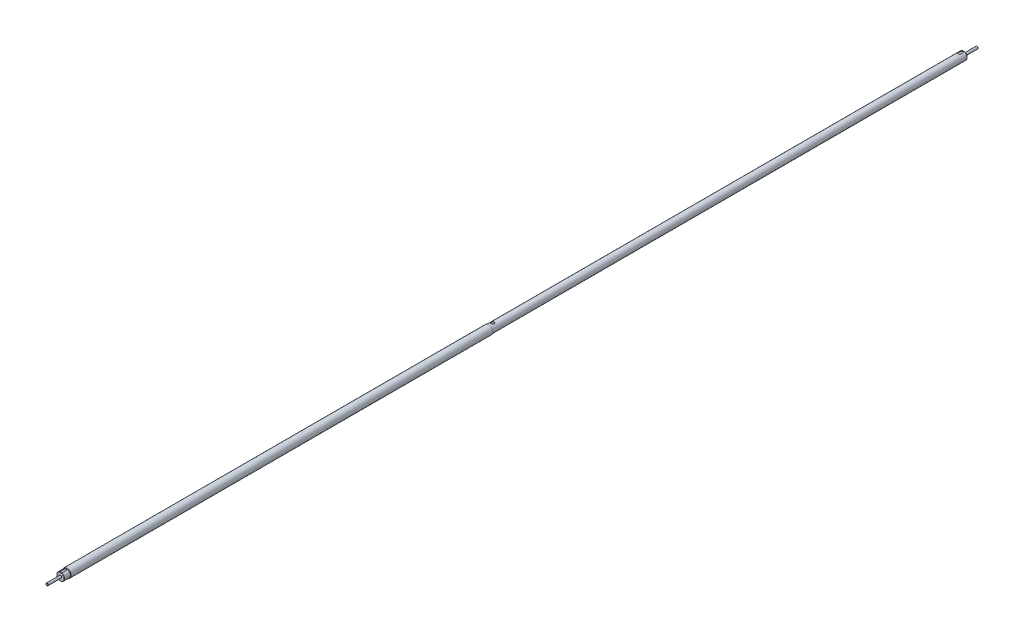
SolidWorks part; units mm, degrees
ref_plane "Спереди" through (0, 0, 0) normal (0, 0, 1) x (1, 0, 0)
ref_plane "Сверху" through (0, 0, 0) normal (0, 1, 0) x (1, 0, 0)
ref_plane "Справа" through (0, 0, 0) normal (1, 0, 0) x (0, 0, -1)
sketch "Эскиз1" plane through (0, 0, 0) normal (1, 0, 0) x (0, 0, -1)
  line L0 (0, 0) -> (0, 3)
  line L1 (0, 3) -> (35, 3)
  line L2 (35, 3) -> (35, 10)
  line L3 (35, 10) -> (51, 10)
  line L4 (51, 10) -> (51, 11)
  line L5 (51, 11) -> (1145, 11)
  line L6 (1145, 11) -> (1145, 10)
  line L7 (1145, 10) -> (1185, 10)
  line L8 (0, 0) -> (2410, 0)
  line L9 (2410, 0) -> (2410, 3)
  line L10 (2410, 3) -> (2375, 3)
  line L11 (2375, 3) -> (2375, 10)
  line L12 (2375, 10) -> (1185, 10)
  dimension "D1" = 3
  dimension "D2" = 7
  dimension "D3" = 35
  dimension "D4" = 16
  dimension "D5" = 1
  dimension "D6" = 1094
  dimension "D7" = 1
  dimension "D8" = 40
  dimension "D9" = 2410
  dimension "D10" = 3
  dimension "D11" = 35
  dimension "D12" = 7
revolve "Повернуть1" add sketch "Эскиз1" angle 360 about L8
ref_plane "Плоскость1" through (0, 10, 0) normal (0, 1, 0) x (1, 0, 0)
sketch "Эскиз2" plane through (0, 10, 0) normal (0, 1, 0) x (1, 0, 0)
  line L0 (0, 47) -> (0, 39) construction
  line L1 (3, 47) -> (3, 39)
  line L2 (-3, 47) -> (-3, 39)
  line L3 (-10, 35) -> (10, 35) construction
  arc A0 (3, 47) -> (-3, 47) centre (0, 47) ccw
  arc A1 (-3, 39) -> (3, 39) centre (0, 39) ccw
  point P3 (0, 43)
  dimension "D1" = 6
  dimension "D2" = 8
  dimension "D3" = 4
extrude "Вырез-Вытянуть1" cut sketch "Эскиз2" against normal blind 1.2 contours L1 A1 L2 A0
ref_plane "Плоскость2" through (0, 10, 0) normal (0, 1, 0) x (1, 0, 0)
sketch "Эскиз3" plane through (0, 10, 0) normal (0, 1, 0) x (1, 0, 0)
  line L0 (0, 2371) -> (0, 2363) construction
  line L1 (3, 2371) -> (3, 2363)
  line L2 (-3, 2371) -> (-3, 2363)
  line L3 (10, 2375) -> (-10, 2375) construction
  arc A0 (3, 2371) -> (-3, 2371) centre (0, 2371) ccw
  arc A1 (-3, 2363) -> (3, 2363) centre (0, 2363) ccw
  point P3 (0, 2367)
  dimension "D1" = 6
  dimension "D2" = 8
  dimension "D3" = 4
extrude "Вырез-Вытянуть2" cut sketch "Эскиз3" against normal blind 1.2 contours L1 A1 L2 A0
ref_plane "Плоскость3" through (0, 10, 0) normal (0, 1, 0) x (1, 0, 0)
sketch "Эскиз4" plane through (0, 10, 0) normal (0, 1, 0) x (1, 0, 0)
  line L0 (10, 1145) -> (-10, 1145) construction
  line L1 (10, 1145) -> (10, 2375) construction
  circle A0 centre (0, 1155) radius 4
  point P2 (0, 0)
  point P5 (0, 0)
  dimension "D1" = 8
  dimension "D2" = 10
  dimension "D3" = 10
extrude "Вырез-Вытянуть3" cut sketch "Эскиз4" against normal blind 10
chamfer "Фаска1" distance 0.5 angle 45 3 edges at (11, 0, -51) (10, 0, -35) (3, 0, 0)
fillet "Скругление1" radius 0.2 1 edges at (10, 0, -51)
fillet "Скругление2" radius 0.2 1 edges at (10, 0, -1145)
chamfer "Фаска2" distance 0.5 angle 45 1 edges at (11, 0, -1145)
chamfer "Фаска3" distance 0.5 angle 45 2 edges at (3, 0, -2410) (10, 0, -2375)
fillet "Скругление3" radius 0.2 1 edges at (3, 0, -2375)
